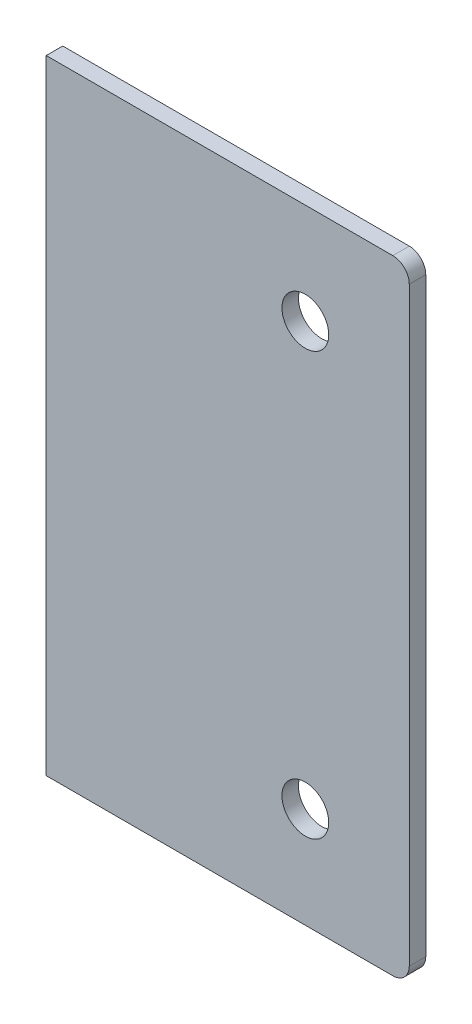
SolidWorks part; units mm, degrees
material "Custom Plastic"
ref_plane "X-Y Datum" through (0, 0, 0) normal (0, 0, 1) x (1, 0, 0)
ref_plane "X-Z Datum" through (0, 0, 0) normal (0, 1, 0) x (1, 0, 0)
ref_plane "Y-Z Datum" through (0, 0, 0) normal (1, 0, 0) x (0, 0, -1)
sketch "Sketch1" plane through (0, 0, 0) normal (0, 0, 1) x (1, 0, 0)
  line L0 (9.3859, 13.274) -> (-10.6141, 13.274) construction
  line L5 (9.3859, 73.274) -> (-25.5391, 73.274)
  line L6 (9.3859, 73.274) -> (9.3859, 13.274)
  line L7 (9.3859, 13.274) -> (-25.5391, 13.274)
  line L8 (-25.5391, 73.274) -> (-25.5391, 13.274)
  line L11 (-10.6141, 73.274) -> (9.3859, 73.274) construction
  line L13 (9.3859, 73.274) -> (9.3859, 13.274) construction
  circle A0 centre (-0.6141, 22.954) radius 3.025 construction
  circle A1 centre (-0.6141, 63.594) radius 3.025 construction
  circle A2 centre (-0.6141, 22.954) radius 3.025 construction
  circle A3 centre (-0.6141, 63.594) radius 3.025 construction
  dimension "D1" = 34.925
extrude "Boss-Extrude1" add sketch "Sketch1" against normal blind 1.5875
hole_wizard "M4 Clearance Hole1" positions "Sketch8" profile "Sketch9" hole size "M4" standard "ANSI Metric" end condition through all
sketch "Sketch8" plane through (0, 0, -1.5875) normal (0, 0, -1) x (-1, 0, 0)
  point P0 (0.6141, 63.594)
  point P3 (0.6141, 22.954)
sketch "Sketch9" plane through (-0.6141, 63.594, -1.5875) normal (1, 0, 0) x (0, 1, 0)
  line L0 (0, 0) -> (0, 1.5875)
  line L1 (0, 1.5875) -> (2.25, 1.5875)
  line L2 (2.25, 1.5875) -> (2.25, 0)
  line L5 (2.25, 0) -> (0, 0)
  line L11 (0, -6.35) -> (0, 107.95) construction
  dimension "Thru Hole Dia." = 4.5
  dimension "Thru Hole Depth" = 1.5875
fillet "Fillet1" radius 1.5875 2 edges at (9.3859, 13.274, -0.7937) (9.3859, 73.274, -0.7937)
